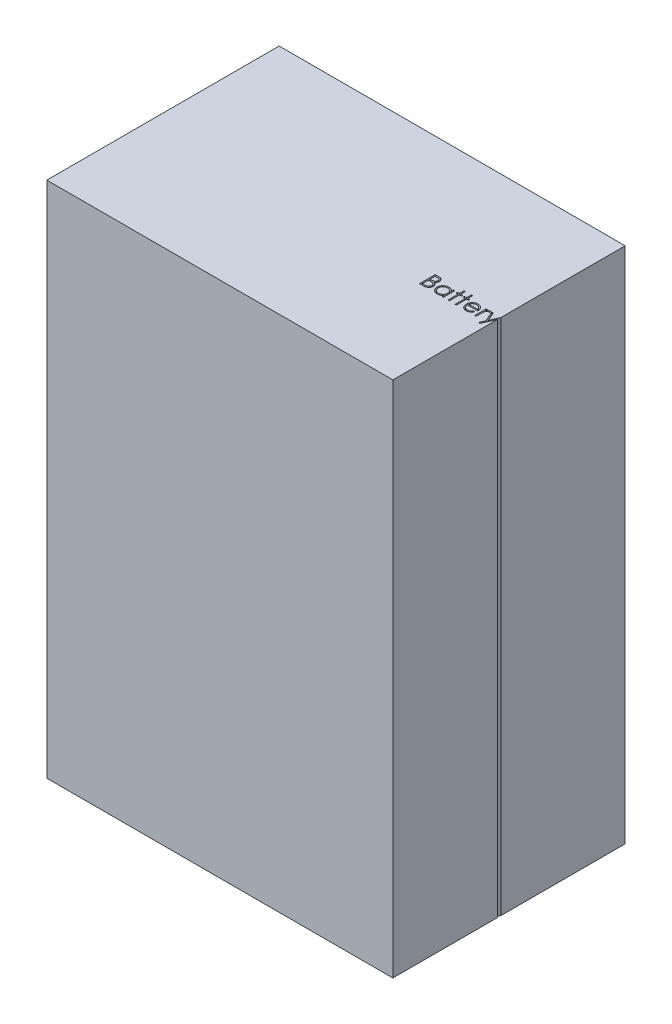
SolidWorks part; units mm, degrees
material "Lithium Ion Battery"
ref_plane "Front Plane" through (0, 0, 0) normal (0, 0, 1) x (1, 0, 0)
ref_plane "Top Plane" through (0, 0, 0) normal (0, 1, 0) x (1, 0, 0)
ref_plane "Right Plane" through (0, 0, 0) normal (1, 0, 0) x (0, 0, -1)
sketch "Sketch1" plane through (0, 0, 0) normal (0, 0, 1) x (1, 0, 0)
  line L0 (35, 0) -> (0, 0) construction
  line L1 (-35, -52.3943) -> (35, -52.3943)
  line L2 (-35, -52.3943) -> (-35, 52.3943)
  line L3 (-35, 52.3943) -> (35, 52.3943)
  line L4 (35, -52.3943) -> (35, 52.3943)
  line L5 (0, 52.3943) -> (0, 0) construction
  dimension "D1" = 70
  dimension "D2" = 104.7887
extrude "Extrude1" add sketch "Sketch1" along normal mid plane 47
sketch "Sketch2" plane through (0, 52.3943, 0) normal (0, 1, 0) x (1, 0, 0)
  text T0 "Battery"
extrude "Extrude2" cut sketch "Sketch2" against normal through all
